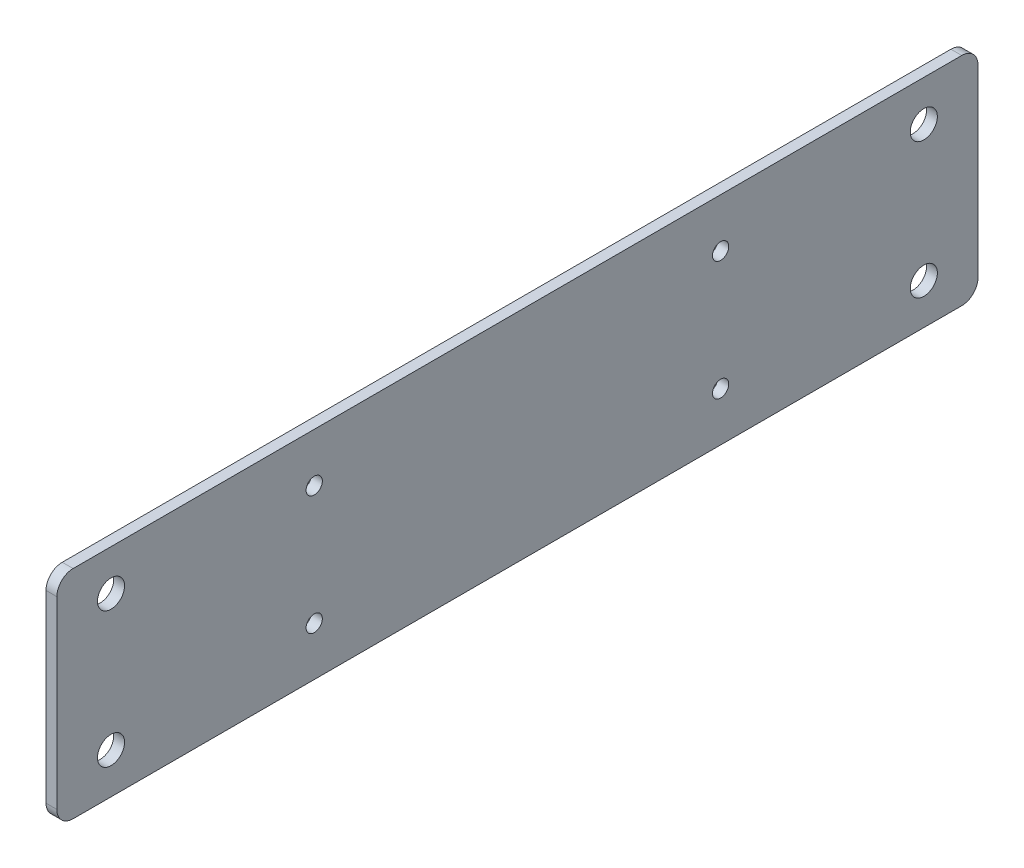
SolidWorks part; units mm, degrees
material "6061 合金"
ref_plane "前视基准面" through (0, 0, 0) normal (0, 0, 1) x (1, 0, 0)
ref_plane "上视基准面" through (0, 0, 0) normal (0, 1, 0) x (1, 0, 0)
ref_plane "右视基准面" through (0, 0, 0) normal (1, 0, 0) x (0, 0, -1)
sketch "草图1" plane through (0, 0, 0) normal (1, 0, 0) x (0, 0, -1)
  line L1 (-85, 20) -> (85, 20)
  line L2 (-85, 20) -> (-85, -20)
  line L3 (-85, -20) -> (85, -20)
  line L4 (85, 20) -> (85, -20)
  line L5 (-85, 20) -> (85, -20) construction
  line L6 (-85, -20) -> (85, 20) construction
  point P0 (0, 0)
  dimension "D1" = 40
  dimension "D2" = 170
extrude "凸台-拉伸1" add sketch "草图1" along normal blind 2
sketch "草图2" plane through (2, 0, 0) normal (1, 0, 0) x (0, 0, -1)
  line L0 (-93.169, 0) -> (118.5628, 0) construction
  line L1 (-85, 20) -> (-85, -20) construction
  line L2 (0, 53.8524) -> (0, -62.2586) construction
  circle A0 centre (-75, 12.5) radius 2.5
  circle A1 centre (-75, -12.5) radius 2.5
  circle A2 centre (75, -12.5) radius 2.5
  circle A3 centre (75, 12.5) radius 2.5
  dimension "D1" = 5
  dimension "D2" = 25
  dimension "D3" = 10
extrude "切除-拉伸1" cut sketch "草图2" against normal through all
sketch "草图3" plane through (2, 0, 0) normal (1, 0, 0) x (0, 0, -1)
  line L2 (-37.5, 11) -> (37.5, 11) construction
  line L3 (-37.5, 11) -> (-37.5, -11) construction
  line L4 (-37.5, -11) -> (37.5, -11) construction
  line L5 (37.5, 11) -> (37.5, -11) construction
  line L6 (-37.5, 11) -> (37.5, -11) construction
  line L7 (-37.5, -11) -> (37.5, 11) construction
  circle A0 centre (-37.5, 11) radius 1.5
  circle A1 centre (-37.5, -11) radius 1.5
  circle A2 centre (37.5, 11) radius 1.5
  circle A3 centre (37.5, -11) radius 1.5
  point P0 (0, 0)
  dimension "D3" = 3
  dimension "D4" = 3
  dimension "D5" = 3
  dimension "D6" = 3
  dimension "D1" = 22
  dimension "D2" = 75
extrude "切除-拉伸2" cut sketch "草图3" against normal through all
fillet "圆角1" radius 3 4 edges at (1, -20, -85) (1, -20, 85) (1, 20, -85) (1, 20, 85)
